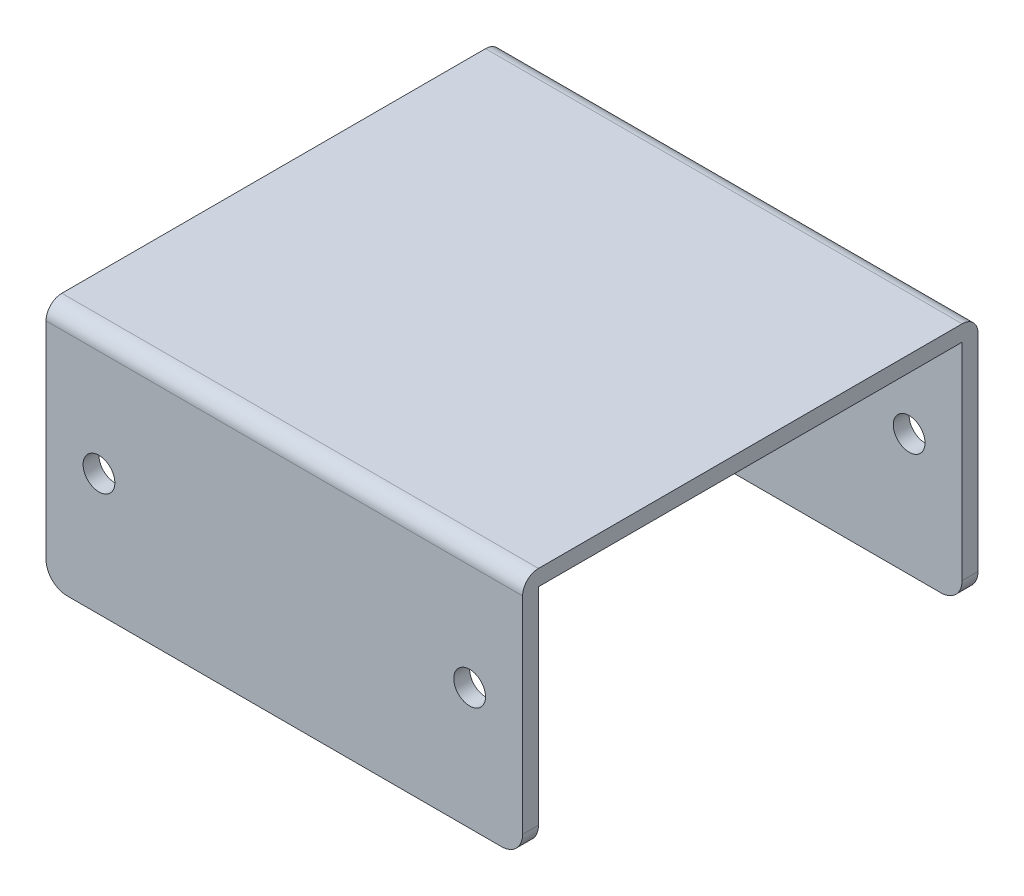
SolidWorks part; units mm, degrees
ref_plane "Front" through (0, 0, 0) normal (0, 0, 1) x (1, 0, 0)
ref_plane "Top" through (0, 0, 0) normal (0, 1, 0) x (1, 0, 0)
ref_plane "Right" through (0, 0, 0) normal (1, 0, 0) x (0, 0, -1)
sketch "草图1" plane through (0, 0, 0) normal (0, 1, 0) x (1, 0, 0)
  line L1 (22.5, -21.5) -> (-22.5, -21.5)
  line L2 (22.5, -21.5) -> (22.5, 21.5)
  line L3 (22.5, 21.5) -> (-22.5, 21.5)
  line L4 (-22.5, -21.5) -> (-22.5, 21.5)
  line L5 (22.5, -21.5) -> (-22.5, 21.5) construction
  line L6 (22.5, 21.5) -> (-22.5, -21.5) construction
  point P0 (0, 0)
  dimension "D1" = 45
  dimension "D2" = 43
extrude "凸台-拉伸1" add sketch "草图1" along normal blind 23
shell "抽壳1" thickness 1.5
sketch "草图2" plane through (0, 0, 21.5) normal (0, 0, 1) x (1, 0, 0)
  line L0 (-22.5, 11.5) -> (22.5, 11.5) construction
  line L1 (-22.5, 23) -> (-22.5, 0) construction
  line L2 (22.5, 23) -> (22.5, 0) construction
  line L3 (0, 23) -> (0, 0) construction
  line L4 (-22.5, 23) -> (22.5, 23) construction
  line L5 (-22.5, 0) -> (22.5, 0) construction
  circle A0 centre (-17.5, 11.5) radius 1.5
  circle A1 centre (17.5, 11.5) radius 1.5
  point P16 (0, 0)
  dimension "D1" = 3
  dimension "D2" = 3
  dimension "D3" = 5
extrude "切除-拉伸1" cut sketch "草图2" against normal through all
fillet "圆角1" radius 1.5 2 edges at (0, 23, -21.5) (0, 23, 21.5)
fillet "圆角2" radius 2 4 edges at (22.5, 0, -20.75) (22.5, 0, 20.75) (-22.5, 0, -20.75) (-22.5, 0, 20.75)
